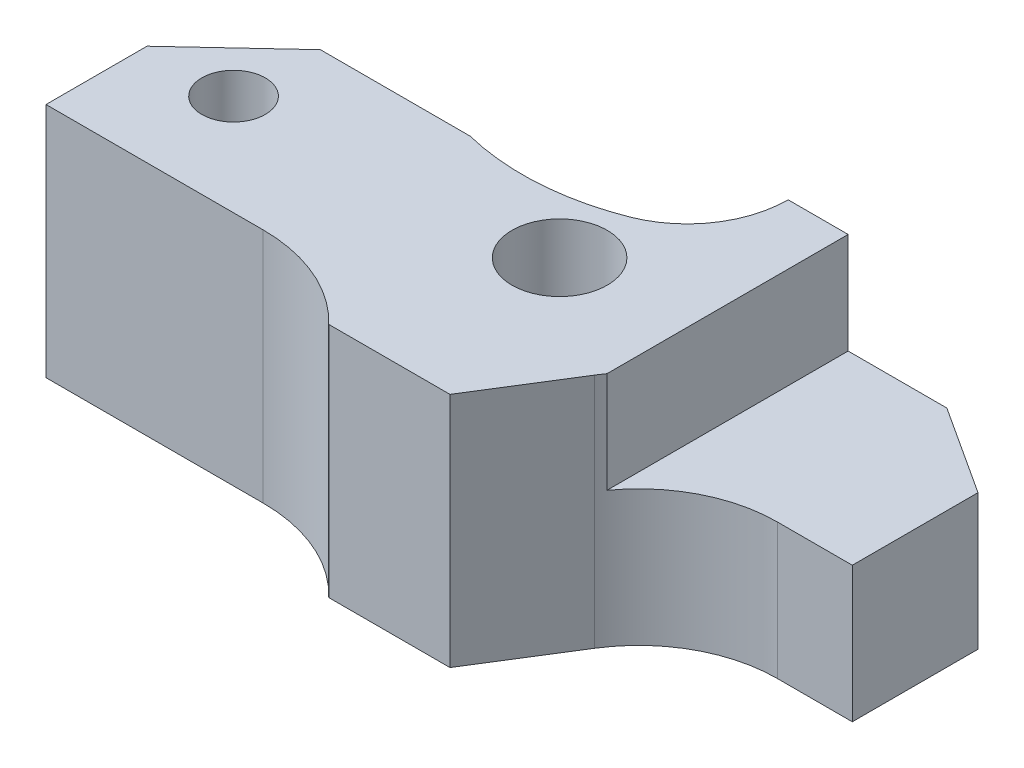
SolidWorks part; units mm, degrees
material "AISI 1020"
ref_plane "Front Plane" through (0, 0, 0) normal (0, 0, 1) x (1, 0, 0)
ref_plane "Top Plane" through (0, 0, 0) normal (0, 1, 0) x (1, 0, 0)
ref_plane "Right Plane" through (0, 0, 0) normal (1, 0, 0) x (0, 0, -1)
sketch "Sketch1" plane through (0, 0, 0) normal (0, 1, 0) x (1, 0, 0)
  line L0 (157.2027, 100) -> (212.2027, 100)
  line L1 (212.2027, 100) -> (243, 80)
  line L2 (243, 80) -> (243, 36.4402)
  line L3 (243, 36.4402) -> (217, 36.4402)
  line L4 (176.2937, 13.8764) -> (157, -17)
  line L5 (157, -17) -> (115, -17)
  line L6 (75.2382, 0) -> (0, 0)
  line L7 (0, 0) -> (0, 35)
  line L8 (0, 35) -> (31.0987, 64)
  line L9 (83, 64) -> (31.0987, 64)
  line L10 (212.2027, 100) -> (32.6444, 100) construction
  line L11 (243, 80) -> (243, -2.5299) construction
  line L12 (157, -17) -> (115, -17) construction
  line L13 (35.4764, -17) -> (30.2288, -17) construction
  line L14 (0, 35) -> (0, 90.8289) construction
  circle A0 centre (135, 43) radius 16.5
  arc A2 (243, 28.7887) -> (176.2937, 13.8764) centre (217, -11.5598) ccw
  arc A3 (115, -17) -> (75.2382, 0) centre (75.2382, -55) ccw
  arc A4 (134.9892, 67.4192) -> (157.2027, 100) centre (122.2027, 100) ccw
  arc A6 (83, 64) -> (134.9892, 67.4192) centre (103.6263, 147.3338) ccw
  dimension "D1" = 33
  dimension "D2" = 96
  dimension "D3" = 17
  dimension "D6" = 110
  dimension "D8" = 70
  dimension "D14" = 42
  dimension "D17" = 102
  dimension "D18" = 81
  dimension "D20" = 83
  dimension "D4" = 85.8485
  dimension "D21" = 47
  dimension "D5" = 35
  dimension "D7" = 117
  dimension "D9" = 55
  dimension "D10" = 57
  dimension "D11" = 97
  dimension "D12" = 60
  dimension "D13" = 58
  dimension "D15" = 115
  dimension "D16" = 20
  dimension "D19" = 128
extrude "Boss-Extrude1" add sketch "Sketch1" along normal blind 82 contours A6 L9 L8 L7 L6 A3 L5 L4 A2 L3 L2 L1 L0 A4 A0
sketch "Sketch2" plane through (0, 82, 0) normal (0, 1, 0) x (1, 0, 0)
  circle A0 centre (30, 35) radius 11
  dimension "D1" = 22
  dimension "D2" = 35
  dimension "D3" = 30
extrude "Cut-Extrude1" cut sketch "Sketch2" against normal through all contours A0
sketch "Sketch5" plane through (0, 0, -100) normal (0, 0, -1) x (-1, 0, 0)
  line L0 (-157.2027, 82) -> (-212.2027, 82) construction
  line L1 (-178, 82) -> (-243, 82)
  line L2 (-178, 82) -> (-178, 47)
  line L3 (-178, 47) -> (-243, 47)
  line L4 (-243, 82) -> (-243, 47)
  line L5 (-243, 82) -> (-243, 0) construction
  dimension "D1" = 65
extrude "Cut-Extrude2" cut sketch "Sketch5" against normal through all
ref_plane "Plane1" through (0, 15, 0) normal (0, -1, 0) x (-1, 0, 0)
sketch "Sketch6" plane through (0, 15, 0) normal (0, -1, 0) x (-1, 0, 0)
  line L0 (0, 0) -> (0, 35) construction
  line L1 (-83, 64) -> (-31.0987, 64) construction
  line L2 (0, 12) -> (0, 35)
  line L3 (-74.6896, 64) -> (-31.0987, 64)
  line L4 (0, 35) -> (-31.0987, 64) construction
  line L5 (0, 35) -> (-31.0987, 64)
  arc A1 (-74.6896, 64) -> (0, 12) centre (-15, 70.0948) ccw
  point P6 (0, 12)
  point P8 (0, 0)
  dimension "D1" = 120
  dimension "D2" = 100
  dimension "D3" = 12
extrude "Cut-Extrude3" cut sketch "Sketch6" against normal blind 40
